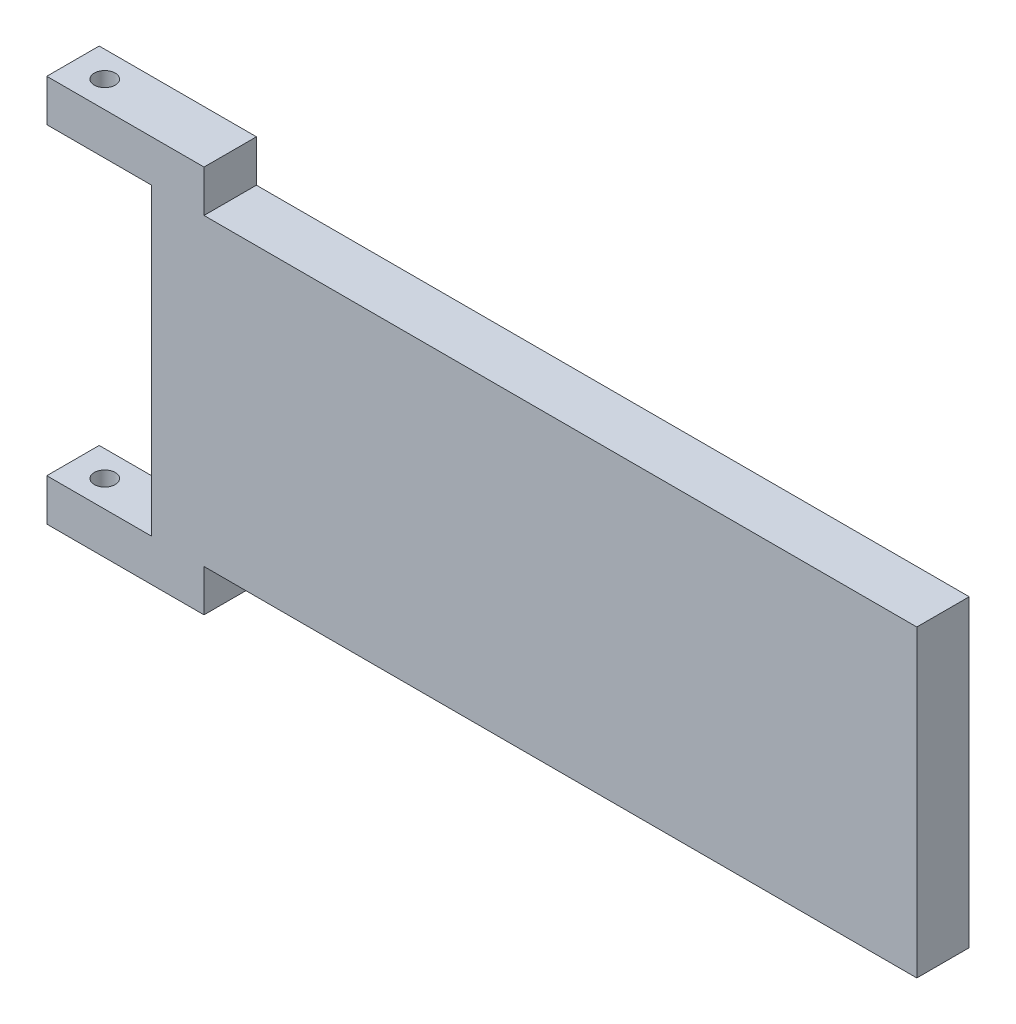
SolidWorks part; units mm, degrees
material "Copper"
ref_plane "Front Plane" through (0, 0, 0) normal (0, 0, 1) x (1, 0, 0)
ref_plane "Top Plane" through (0, 0, 0) normal (0, 1, 0) x (1, 0, 0)
ref_plane "Right Plane" through (0, 0, 0) normal (1, 0, 0) x (0, 0, -1)
sketch "Sketch1" plane through (0, 0, 0) normal (0, 0, 1) x (1, 0, 0)
  line L1 (0, 0) -> (73, 0)
  line L2 (0, 0) -> (0, 29)
  line L3 (0, 29) -> (73, 29)
  line L4 (73, 0) -> (73, 29)
  line L5 (5, 29) -> (-10, 29)
  line L6 (5, 29) -> (5, 33)
  line L7 (5, 33) -> (-10, 33)
  line L8 (-10, 29) -> (-10, 33)
  line L9 (5, 0) -> (-10, 0)
  line L10 (5, 0) -> (5, -4)
  line L11 (5, -4) -> (-10, -4)
  line L12 (-10, 0) -> (-10, -4)
  dimension "D1" = 73
  dimension "D2" = 29
  dimension "D3" = 5
  dimension "D4" = 5
  dimension "D5" = 15
  dimension "D6" = 4
extrude "Boss-Extrude1" add sketch "Sketch1" along normal blind 5 contours L1 L4 L3 L2 | L8 L5 L3 L6 L7 | L9 L12 L11 L10 L1
sketch "Sketch2" plane through (0, 33, 0) normal (0, 1, 0) x (1, 0, 0)
  line L0 (-10, -5) -> (-10, 0) construction
  circle A0 centre (-7, -2.4694) radius 1
  dimension "D1" = 3
  dimension "D2" = 2
extrude "Cut-Extrude1" cut sketch "Sketch2" against normal blind 35
